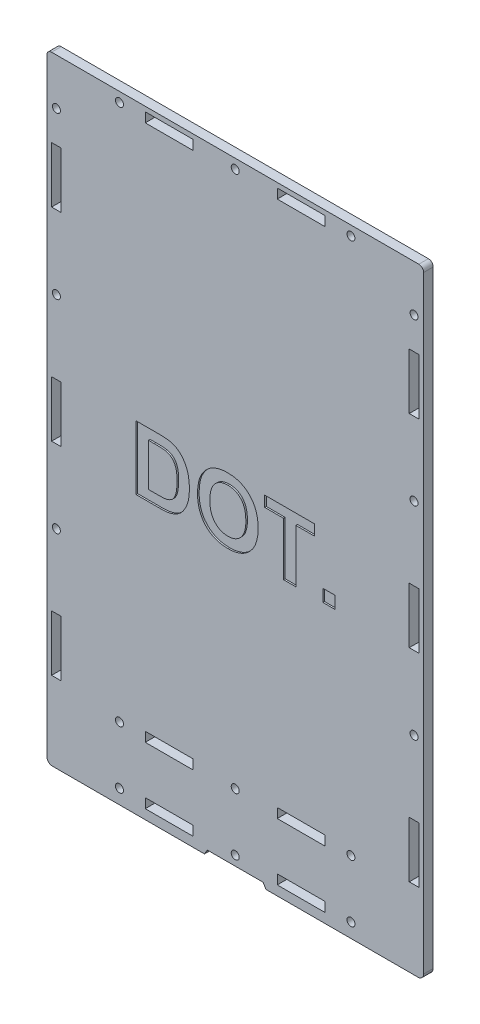
SolidWorks part; units mm, degrees
ref_plane "Спереди" through (0, 0, 0) normal (0, 0, 1) x (1, 0, 0)
ref_plane "Сверху" through (0, 0, 0) normal (0, 1, 0) x (1, 0, 0)
ref_plane "Справа" through (0, 0, 0) normal (1, 0, 0) x (0, 0, -1)
sketch "Эскиз1" plane through (0, 0, 0) normal (0, 0, 1) x (1, 0, 0)
  line L0 (0, 0) -> (0, 50000) construction
  line L1 (-56.3333, -372) -> (-26.3333, -372) construction
  line L2 (-26.3333, -372) -> (-26.3333, -366) construction
  line L3 (-26.3333, -366) -> (-56.3333, -366) construction
  line L4 (-56.3333, -366) -> (-56.3333, -372) construction
  line L5 (-56.3333, -336) -> (-26.3333, -336) construction
  line L6 (-26.3333, -336) -> (-26.3333, -330) construction
  line L7 (-26.3333, -330) -> (-56.3333, -330) construction
  line L8 (-56.3333, -330) -> (-56.3333, -336) construction
  line L9 (-109, -329) -> (-109, -294) construction
  line L10 (-109, -294) -> (-115, -294) construction
  line L11 (-115, -294) -> (-115, -329) construction
  line L12 (-115, -329) -> (-109, -329) construction
  line L13 (-109, -202) -> (-109, -167) construction
  line L14 (-109, -167) -> (-115, -167) construction
  line L15 (-115, -167) -> (-115, -202) construction
  line L16 (-115, -202) -> (-109, -202) construction
  line L17 (-109, -75) -> (-109, -40) construction
  line L18 (-109, -40) -> (-115, -40) construction
  line L19 (-115, -40) -> (-115, -75) construction
  line L20 (-115, -75) -> (-109, -75) construction
  line L21 (-56.3333, 0) -> (-26.3333, 0) construction
  line L22 (-26.3333, 0) -> (-26.3333, 6) construction
  line L23 (-26.3333, 6) -> (-56.3333, 6) construction
  line L24 (-56.3333, 6) -> (-56.3333, 0) construction
  line L25 (-56.3333, -372) -> (-26.3333, -372)
  line L26 (-26.3333, -372) -> (-26.3333, -366)
  line L27 (-26.3333, -366) -> (-56.3333, -366)
  line L28 (-56.3333, -366) -> (-56.3333, -372)
  line L29 (-56.3333, -336) -> (-26.3333, -336)
  line L30 (-26.3333, -336) -> (-26.3333, -330)
  line L31 (-26.3333, -330) -> (-56.3333, -330)
  line L32 (-56.3333, -330) -> (-56.3333, -336)
  line L33 (-109, -329) -> (-109, -294)
  line L34 (-109, -294) -> (-115, -294)
  line L35 (-115, -294) -> (-115, -329)
  line L36 (-115, -329) -> (-109, -329)
  line L37 (-109, -202) -> (-109, -167)
  line L38 (-109, -167) -> (-115, -167)
  line L39 (-115, -167) -> (-115, -202)
  line L40 (-115, -202) -> (-109, -202)
  line L41 (-109, -75) -> (-109, -40)
  line L42 (-109, -40) -> (-115, -40)
  line L43 (-115, -40) -> (-115, -75)
  line L44 (-115, -75) -> (-109, -75)
  line L45 (-56.3333, 0) -> (-26.3333, 0)
  line L46 (-26.3333, 0) -> (-26.3333, 6)
  line L47 (-26.3333, 6) -> (-56.3333, 6)
  line L48 (-56.3333, 6) -> (-56.3333, 0)
  line L49 (-74.95, 3) -> (-70.05, 3) construction
  line L50 (-74.95, 6) -> (-74.95, 0) construction
  line L51 (-70.05, 6) -> (-70.05, 0) construction
  line L52 (-112, -17.55) -> (-112, -22.45) construction
  line L53 (-115, -17.55) -> (-109, -17.55) construction
  line L54 (-115, -22.45) -> (-109, -22.45) construction
  line L55 (2.45, 3) -> (-2.45, 3) construction
  line L56 (-115, -118.55) -> (-109, -118.55) construction
  line L57 (-112, -118.55) -> (-112, -123.45) construction
  line L58 (-115, -123.45) -> (-109, -123.45) construction
  line L59 (2.45, 6) -> (2.45, 0) construction
  line L60 (-115, -245.55) -> (-109, -245.55) construction
  line L61 (-112, -245.55) -> (-112, -250.45) construction
  line L62 (-115, -250.45) -> (-109, -250.45) construction
  line L63 (-2.45, 6) -> (-2.45, 0) construction
  line L65 (-115, -378) -> (-109, -378) construction
  line L67 (74.95, -369) -> (70.05, -369) construction
  line L68 (-74.95, -330) -> (-74.95, -336) construction
  line L69 (-74.95, -333) -> (-70.05, -333) construction
  line L70 (-70.05, -330) -> (-70.05, -336) construction
  line L71 (74.95, -333) -> (70.05, -333) construction
  line L72 (-74.95, -366) -> (-74.95, -372) construction
  line L73 (-74.95, -369) -> (-70.05, -369) construction
  line L74 (-70.05, -366) -> (-70.05, -372) construction
  line L76 (-2.45, -330) -> (-2.45, -336) construction
  line L77 (-2.45, -333) -> (2.45, -333) construction
  line L78 (2.45, -330) -> (2.45, -336) construction
  line L79 (112, -245.55) -> (112, -250.45) construction
  line L80 (-2.45, -366) -> (-2.45, -372) construction
  line L81 (-2.45, -369) -> (2.45, -369) construction
  line L82 (2.45, -366) -> (2.45, -372) construction
  line L83 (112, -118.55) -> (112, -123.45) construction
  line L84 (112, -17.55) -> (112, -22.45) construction
  line L85 (74.95, 3) -> (70.05, 3) construction
  line L86 (56.3333, 6) -> (56.3333, 0)
  line L87 (26.3333, 6) -> (56.3333, 6)
  line L88 (26.3333, 0) -> (26.3333, 6)
  line L89 (56.3333, 0) -> (26.3333, 0)
  line L90 (115, -75) -> (109, -75)
  line L91 (115, -40) -> (115, -75)
  line L92 (109, -40) -> (115, -40)
  line L93 (109, -75) -> (109, -40)
  line L94 (115, -202) -> (109, -202)
  line L95 (115, -167) -> (115, -202)
  line L96 (109, -167) -> (115, -167)
  line L97 (109, -202) -> (109, -167)
  line L98 (115, -329) -> (109, -329)
  line L99 (115, -294) -> (115, -329)
  line L100 (109, -294) -> (115, -294)
  line L101 (109, -329) -> (109, -294)
  line L102 (56.3333, -330) -> (56.3333, -336)
  line L103 (26.3333, -330) -> (56.3333, -330)
  line L104 (26.3333, -336) -> (26.3333, -330)
  line L105 (56.3333, -336) -> (26.3333, -336)
  line L106 (56.3333, -366) -> (56.3333, -372)
  line L107 (26.3333, -366) -> (56.3333, -366)
  line L108 (26.3333, -372) -> (26.3333, -366)
  line L109 (56.3333, -372) -> (26.3333, -372)
  line L110 (-118, 9) -> (118, 9)
  line L111 (-118, 9) -> (-118, -378)
  line L112 (-118, -378) -> (118, -378) construction
  line L113 (118, 9) -> (118, -378)
  line L114 (-115, 9) -> (-109, 9) construction
  line L116 (-118, -378) -> (-19.2321, -378)
  line L117 (-19.2321, -378) -> (-17.5, -375)
  line L118 (-17.5, -375) -> (17.5, -375)
  line L119 (118, -378) -> (19.2321, -378)
  line L120 (19.2321, -378) -> (17.5, -375)
  circle A0 centre (0, 3) radius 2.5
  circle A1 centre (-72.5, 3) radius 2.5
  circle A2 centre (-112, -20) radius 2.5
  circle A3 centre (-112, -121) radius 2.5
  circle A4 centre (-112, -248) radius 2.5
  circle A6 centre (-72.5, -369) radius 2.5
  circle A7 centre (-72.5, -333) radius 2.5
  circle A8 centre (0, -333) radius 2.5
  circle A9 centre (0, -369) radius 2.5
  circle A10 centre (72.5, -333) radius 2.5
  circle A11 centre (72.5, -369) radius 2.5
  circle A13 centre (112, -248) radius 2.5
  circle A14 centre (112, -121) radius 2.5
  circle A15 centre (112, -20) radius 2.5
  circle A16 centre (72.5, 3) radius 2.5
  point P172 (15.3254, -374.9075)
  dimension "D1" = 5
  dimension "D2" = 3
  dimension "D3" = 3
  dimension "D4" = 60
  dimension "D5" = 35
extrude "Бобышка-Вытянуть1" add sketch "Эскиз1" along normal blind 6
fillet "Скругление1" radius 3.5 2 edges at (-118, -378, 3) (118, -378, 3)
fillet "Скругление2" radius 3 2 edges at (118, 9, 3) (-118, 9, 3)
sketch "Эскиз2" plane through (0, 0, 6) normal (0, 0, 1) x (1, 0, 0)
  line L0 (0, 9) -> (0, -378) construction
  line L1 (115, 9) -> (-115, 9) construction
  line L2 (-114.5, -378) -> (-19.2321, -378) construction
  line L3 (80.6654, -204.5) -> (-80.6654, -204.5) construction
  text T0 "<b>DOT.</b>" font "Arial" height 40
  point P7 (0, -184.5)
  point P10 (0, -204.5)
  point P12 (65.6541, -204.5)
  point P13 (80.6654, -204.5)
  dimension "D1" = 20
extrude "Вырез-Вытянуть1" cut sketch "Эскиз2" against normal blind 1
